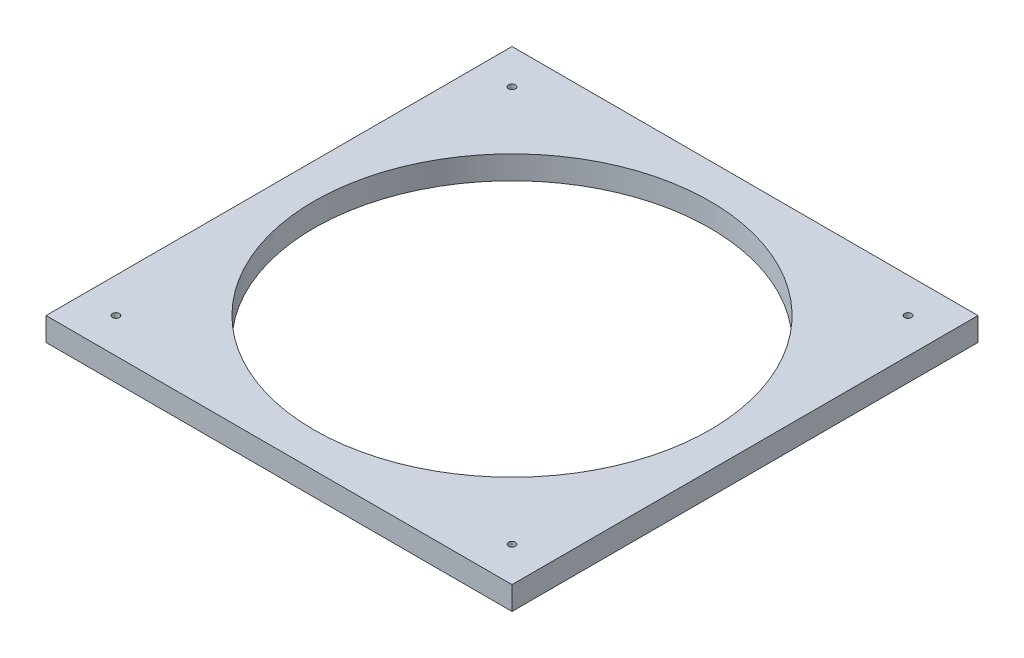
SolidWorks part; units mm, degrees
ref_plane "Front Plane" through (0, 0, 0) normal (0, 0, 1) x (1, 0, 0)
ref_plane "Top Plane" through (0, 0, 0) normal (0, 1, 0) x (1, 0, 0)
ref_plane "Right Plane" through (0, 0, 0) normal (1, 0, 0) x (0, 0, -1)
sketch "Sketch1" plane through (0, 0, 0) normal (0, 1, 0) x (1, 0, 0)
  line L1 (-200, 200) -> (200, 200)
  line L2 (-200, 200) -> (-200, -200)
  line L3 (-200, -200) -> (200, -200)
  line L4 (200, 200) -> (200, -200)
  circle A0 centre (0, 0) radius 170
  circle A1 centre (-170, 170) radius 3
  circle A2 centre (170, 170) radius 3
  circle A3 centre (170, -170) radius 3
  circle A4 centre (-170, -170) radius 3
  point P4 (0, 200)
  point P6 (-200, 0)
  point P20 (0, 0)
  dimension "D3" = 340
  dimension "D4" = 6
  dimension "D1" = 400
  dimension "D2" = 400
  dimension "D5" = 170
  dimension "D6" = 170
extrude "Boss-Extrude1" add sketch "Sketch1" along normal blind 20
